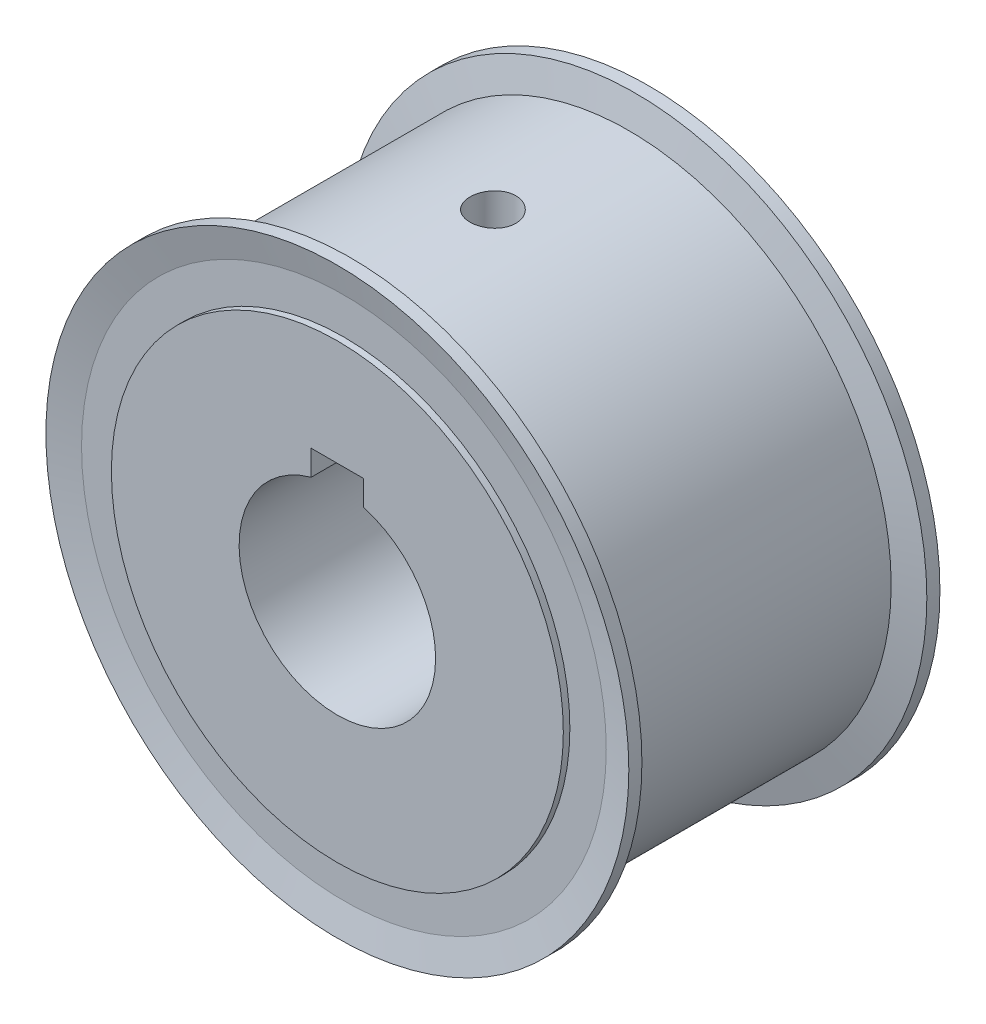
SolidWorks part; units mm, degrees
ref_plane "Front" through (0, 0, 0) normal (0, 0, 1) x (1, 0, 0)
ref_plane "Top" through (0, 0, 0) normal (0, 1, 0) x (1, 0, 0)
ref_plane "Right" through (0, 0, 0) normal (1, 0, 0) x (0, 0, -1)
sketch "Sketch1" plane through (0, 0, 0) normal (1, 0, 0) x (0, 0, -1)
  line L0 (-52.8569, 0) -> (13.5853, 0) construction
  line L1 (-47.5, 34.5) -> (-46.5, 34.5)
  line L2 (-47.5, 34.5) -> (-47.5, 0)
  line L3 (-47.5, 0) -> (0, 0)
  line L4 (-1, 34.5) -> (0, 34.5)
  line L5 (-46.5, 34.5) -> (-46.5, 40.055)
  line L6 (-46.5, 40.055) -> (-47.5, 44.5)
  line L7 (-47.5, 44.5) -> (-45.5, 44.5)
  line L8 (-45.5, 44.5) -> (-44.5, 40.055)
  line L9 (-44.5, 40.055) -> (-3, 40.055)
  line L10 (-3, 40.055) -> (-2, 44.5)
  line L11 (-2, 44.5) -> (0, 44.5)
  line L12 (0, 44.5) -> (-1, 40.055)
  line L13 (-1, 40.055) -> (-1, 34.5)
  line L14 (0, 34.5) -> (0, 0)
  dimension "D1" = 69
  dimension "D2" = 80.11
  dimension "D3" = 89
  dimension "D4" = 47.5
  dimension "D5" = 3
  dimension "D6" = 2
revolve "Revolve1" add sketch "Sketch1" angle 360 about L0
sketch "Sketch2" plane through (0, 0, 0) normal (1, 0, 0) x (0, 0, -1)
  line L0 (27.9721, 0) -> (-88.0606, 0) construction
  line L1 (-47.5, 44.5) -> (-47.5, -44.5) construction
  line L2 (-47.5, 15) -> (0, 15)
  line L3 (-47.5, 15) -> (-47.5, 0)
  line L4 (-47.5, 0) -> (0, 0)
  line L5 (0, 15) -> (0, 0)
  line L6 (0, 44.5) -> (0, -44.5) construction
  dimension "D1" = 30
revolve "Cut-Revolve1" cut sketch "Sketch2" angle 360 about L0
sketch "Sketch3" plane through (0, 0, 47.5) normal (0, 0, 1) x (1, 0, 0)
  line L0 (0, 0) -> (0, 24.8792) construction
  line L1 (-4, 18.3) -> (4, 18.3)
  line L2 (-4, 18.3) -> (-4, 14.4568)
  line L4 (4, 18.3) -> (4, 14.4568)
  circle A0 centre (0, 0) radius 15 construction
  arc A1 (4, 14.4568) -> (-4, 14.4568) centre (0, 0) ccw
  dimension "D1" = 18.3
  dimension "D2" = 8
extrude "Cut-Extrude1" cut sketch "Sketch3" against normal through all
ref_plane "Plane1" through (0, 40.055, 0) normal (0, 1, 0) x (-1, 0, 0)
hole_wizard "Ø7.0 (7) Diameter Hole1" positions "Sketch5" profile "Sketch4" hole size "Ø7.0" standard "JIS"
sketch "Sketch5" plane through (0, 40.055, 0) normal (0, 1, 0) x (-1, 0, 0)
  line L3 (-44.5, 2) -> (44.5, 2) construction
  point P1 (0, 23.75)
  dimension "D1" = 21.75
sketch "Sketch4" plane through (0, 40.055, 23.75) normal (1, 0, 0) x (0, 0, 1)
  line L0 (0, 0) -> (0, 10)
  line L1 (0, 10) -> (3.5, 10)
  line L2 (3.5, 10) -> (3.5, 0)
  line L5 (3.5, 0) -> (0, 0)
  line L10 (0, 10) -> (-3.5, 10) construction
  line L11 (0, -6.35) -> (0, 107.95) construction
  dimension "Hole Dia." = 7
  dimension "Hole Depth" = 10
  dimension "Drill Angle" = 180
hole_wizard "M6x1.0 Tapped Hole1" positions "Sketch7" profile "Sketch6" tap size "M6x1.0" standard "JIS"
sketch "Sketch7" plane through (0, 30.055, 0) normal (0, 1, 0) x (-1, 0, 0)
  point P0 (0, 23.75)
cosmetic thread "Hole Thread1" parameters "D2"=6
sketch "Sketch6" plane through (0, 30.055, 23.75) normal (1, 0, 0) x (0, 0, 1)
  line L0 (0, 0) -> (0, 70.11)
  line L1 (0, 70.11) -> (2.5, 70.11)
  line L2 (2.5, 70.11) -> (2.5, 0)
  line L5 (2.5, 0) -> (0, 0)
  line L11 (0, -6.35) -> (0, 107.95) construction
  dimension "Thru Tap Drill Dia." = 5
  dimension "Thru Tap Drill Depth" = 70.11
pattern_circular "CirPattern1" count 2 over 120 about axis through (0, 0, -27.9721) along (0, 0, -1) of "Ø7.0 (7) Diameter Hole1", "M6x1.0 Tapped Hole1"
